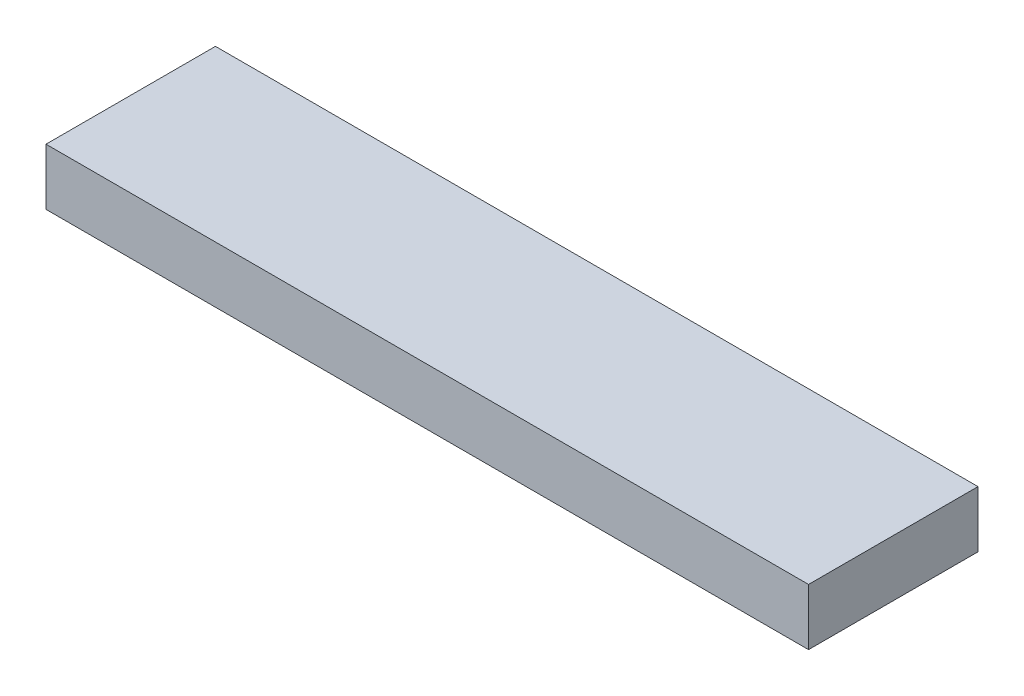
SolidWorks part; units mm, degrees
ref_plane "Front Plane" through (0, 0, 0) normal (0, 0, 1) x (1, 0, 0)
ref_plane "Top Plane" through (0, 0, 0) normal (0, 1, 0) x (1, 0, 0)
ref_plane "Right Plane" through (0, 0, 0) normal (1, 0, 0) x (0, 0, -1)
sketch "Sketch1" plane through (0, 0, 0) normal (0, 1, 0) x (1, 0, 0)
  line L1 (-23.4369, 16.2331) -> (62.2881, 16.2331)
  line L2 (-23.4369, 16.2331) -> (-23.4369, -2.8169)
  line L3 (-23.4369, -2.8169) -> (62.2881, -2.8169)
  line L4 (62.2881, 16.2331) -> (62.2881, -2.8169)
  dimension "D1" = 85.725
  dimension "D2" = 19.05
extrude "Boss-Extrude1" add sketch "Sketch1" along normal blind 6.35
